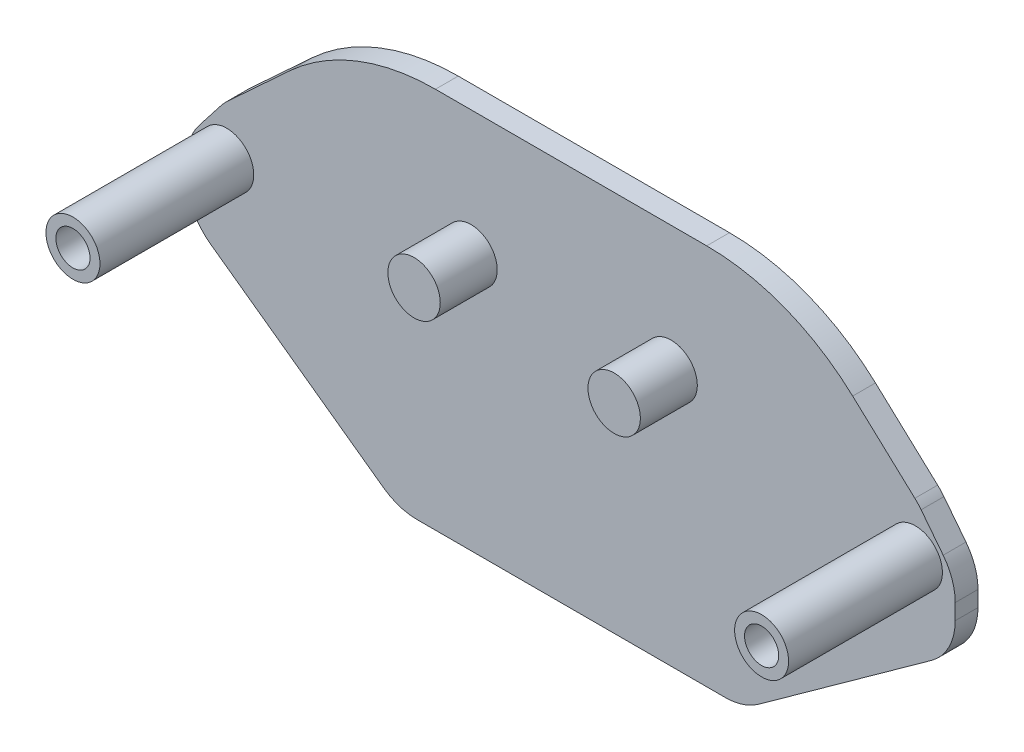
SolidWorks part; units mm, degrees
material "ABS"
ref_plane "Plan de face" through (0, 0, 0) normal (0, 0, 1) x (1, 0, 0)
ref_plane "Plan de dessus" through (0, 0, 0) normal (0, 1, 0) x (1, 0, 0)
ref_plane "Plan de droite" through (0, 0, 0) normal (1, 0, 0) x (0, 0, -1)
sketch "Esquisse1" plane through (0, 0, 0) normal (0, 0, 1) x (1, 0, 0)
  line L0 (31.6406, -4.8872) -> (16.4505, -15.8195)
  line L1 (-24.7195, 11.748) -> (-30.1767, 6.7065)
  line L7 (-30.7275, 6.1076) -> (-32.6635, 3.6237)
  line L8 (-33.7198, 0.55) -> (-33.7198, -0.829)
  line L9 (-31.6406, -4.8872) -> (-16.4505, -15.8195)
  line L10 (33.7198, 0.55) -> (33.7198, -0.829)
  line L11 (30.7275, 6.1076) -> (32.6635, 3.6237)
  line L17 (24.7195, 11.748) -> (30.1767, 6.7065)
  line L18 (0, 16.7612) -> (0, -16.7612) construction
  line L19 (-11.905, 16.7612) -> (11.905, 16.7612)
  line L20 (13.5298, -16.7612) -> (-13.5298, -16.7612)
  arc A0 (-16.4505, -15.8195) -> (-13.5298, -16.7612) centre (-13.5298, -11.7612) ccw
  arc A1 (-33.7198, -0.829) -> (-31.6406, -4.8872) centre (-28.7198, -0.829) ccw
  circle A2 centre (-30.2257, 2.2684) radius 1.5
  arc A3 (-32.6635, 3.6237) -> (-33.7198, 0.55) centre (-28.7198, 0.55) ccw
  arc A6 (-30.1767, 6.7065) -> (-30.7275, 6.1076) centre (-26.7839, 3.0338) ccw
  arc A7 (-11.905, 16.7612) -> (-24.7195, 11.748) centre (-11.905, -2.1232) ccw
  arc A8 (11.905, 16.7612) -> (24.7195, 11.748) centre (11.905, -2.1232) cw
  arc A9 (30.1767, 6.7065) -> (30.7275, 6.1076) centre (26.7839, 3.0338) cw
  arc A12 (32.6635, 3.6237) -> (33.7198, 0.55) centre (28.7198, 0.55) cw
  circle A13 centre (30.2257, 2.2684) radius 1.5
  arc A14 (33.7198, -0.829) -> (31.6406, -4.8872) centre (28.7198, -0.829) cw
  arc A15 (16.4505, -15.8195) -> (13.5298, -16.7612) centre (13.5298, -11.7612) cw
  dimension "D3" = 5
  dimension "D2" = 5
extrude "Boss.-Extru.3" add sketch "Esquisse1" along normal blind 2
sketch "Esquisse2" plane through (0, 0, 55.32) normal (0, 0, 1) x (1, 0, 0)
  circle A0 centre (-8.782, 5.7361) radius 2.3
  circle A1 centre (8.7821, 5.7361) radius 2.3
  dimension "D1" = 4.6
  dimension "D2" = 4.6
extrude "Boss.-Extru.4" add sketch "Esquisse2" along normal blind 5 from surface at -53.32 contours A0 | A1 starting at face at (0, 0.8028, 2)
sketch "Esquisse3" plane through (0, 0, 0) normal (0, 0, -1) x (-1, 0, 0)
  circle A0 centre (60.2396, 19.7622) radius 1.5
  circle A1 centre (-29.9555, 19.7622) radius 1.5
extrude "Enlèv. mat.-Extru.1" cut sketch "Esquisse3" against normal blind 10
sketch "Esquisse4" plane through (0, 0, 2) normal (0, 0, 1) x (1, 0, 0)
  circle A0 centre (30.2257, 2.2684) radius 1.5
  circle A1 centre (30.2257, 2.2684) radius 2.37
  circle A2 centre (-30.2257, 2.2684) radius 1.5
  circle A3 centre (-30.2257, 2.2684) radius 2.37
  dimension "D1" = 4.74
  dimension "D2" = 4.74
extrude "Boss.-Extru.5" add sketch "Esquisse4" along normal blind 13.5
